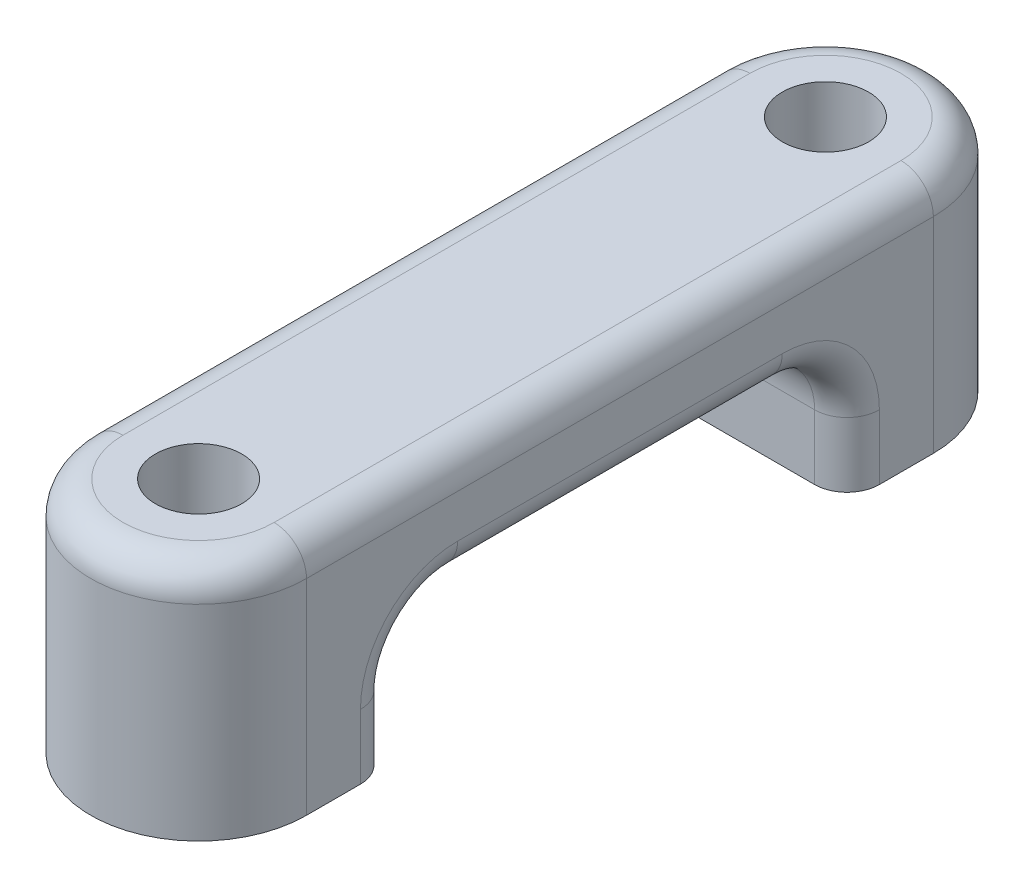
SolidWorks part; units mm, degrees
ref_plane "Alzado" through (0, 0, 0) normal (0, 0, 1) x (1, 0, 0)
ref_plane "Planta" through (0, 0, 0) normal (0, 1, 0) x (1, 0, 0)
ref_plane "Vista lateral" through (0, 0, 0) normal (1, 0, 0) x (0, 0, -1)
sketch "Sketch1" plane through (0, 0, 0) normal (0, 1, 0) x (1, 0, 0)
  line L0 (-5, 0) -> (5, 0) construction
  line L1 (-5, -14.5207) -> (5, -14.5207) construction
  line L2 (-5, -14.5207) -> (-5, 14.5207)
  line L3 (-5, 14.5207) -> (5, 14.5207) construction
  line L4 (5, -14.5207) -> (5, 14.5207)
  line L5 (-5, -14.5207) -> (5, 14.5207) construction
  line L6 (-5, 14.5207) -> (5, -14.5207) construction
  circle A0 centre (0, 14.5207) radius 2
  circle A1 centre (0, -14.5207) radius 2
  arc A2 (-5, 14.5207) -> (5, 14.5207) centre (0, 14.5207) cw
  arc A3 (-5, -14.5207) -> (5, -14.5207) centre (0, -14.5207) ccw
  point P0 (0, 0)
  point P11 (0, 0)
  dimension "D1" = 29.0414
  dimension "D4" = 4
  dimension "D2" = 10
extrude "Boss-Extrude1" add sketch "Sketch1" along normal blind 5
sketch "Sketch2" plane through (0, 0, 0) normal (0, -1, 0) x (1, 0, 0)
  line L0 (-5, -10.5207) -> (5, -10.5207)
  line L5 (-5, 10.5207) -> (5, 10.5207)
  line L6 (5, -14.5207) -> (5, 14.5207)
  line L11 (-5, 14.5207) -> (-5, -14.5207)
  line L12 (5, -14.5207) -> (5, -10.5207)
  line L13 (-5, 14.5207) -> (-5, 10.5207)
  line L14 (-5, -10.5207) -> (-5, -14.5207)
  line L15 (5, 10.5207) -> (5, 14.5207)
  circle A4 centre (0, 14.5207) radius 2 construction
  circle A5 centre (0, 14.5207) radius 2
  arc A6 (-5, -14.5207) -> (5, -14.5207) centre (0, -14.5207) ccw
  arc A7 (5, 14.5207) -> (-5, 14.5207) centre (0, 14.5207) ccw
  arc A8 (-5, -14.5207) -> (5, -14.5207) centre (0, -14.5207) ccw
  arc A9 (5, 14.5207) -> (-5, 14.5207) centre (0, 14.5207) ccw
  circle A10 centre (0, -14.5207) radius 2 construction
  circle A11 centre (0, -14.5207) radius 2
  dimension "D1" = 0
  dimension "D2" = 4
  dimension "D3" = 4
extrude "Boss-Extrude2" add sketch "Sketch2" along normal blind 6
fillet "Fillet2" radius 3 2 edges at (0, 0, -10.5207) (0, 0, 10.5207)
fillet "Fillet1" radius 1.5 14 edges at (5, 0, 0) (-5, 0, 0) (-5, 5, 0) (5, 5, 0) (0, 5, 19.5207) (0, 5, -19.5207) (-5, -4.5, -10.5207) (-5, -0.8787, -9.642) (-5, -4.5, 10.5207) (-5, -0.8787, 9.642) (5, -4.5, 10.5207) (5, -0.8787, 9.642) (5, -4.5, -10.5207) (5, -0.8787, -9.642)
